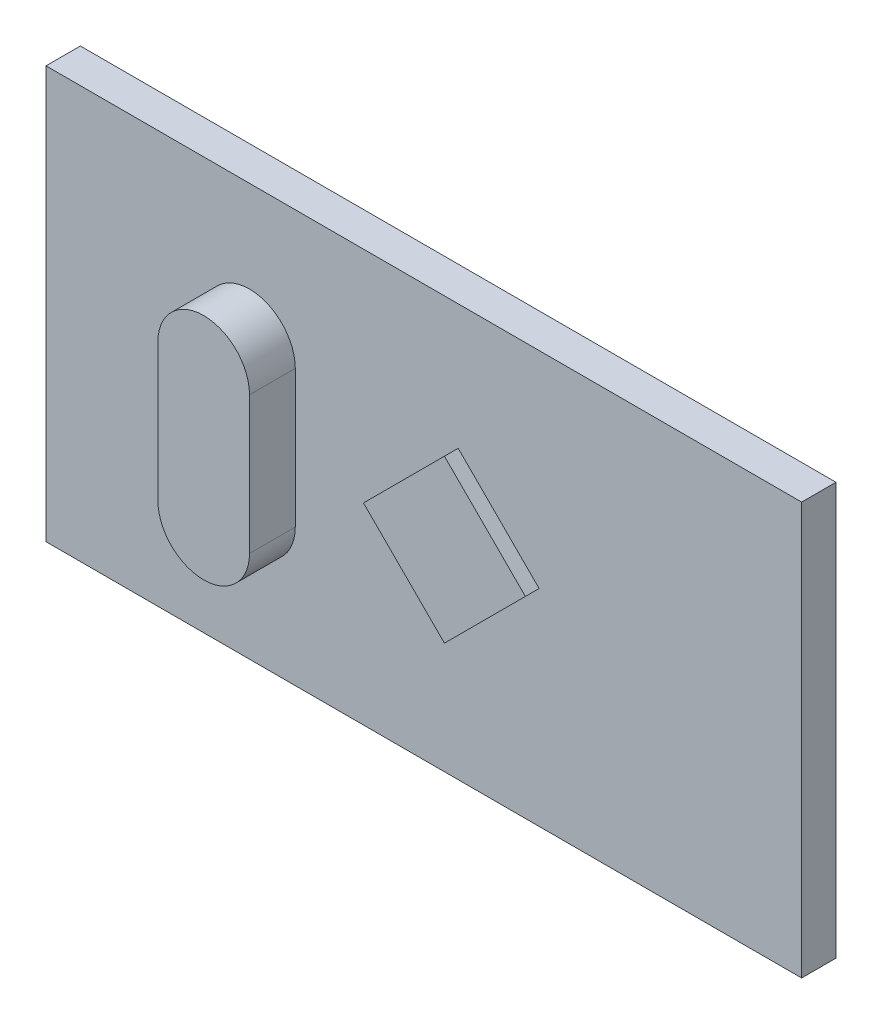
SolidWorks part; units mm, degrees
ref_plane "Спереди" through (0, 0, 0) normal (0, 0, 1) x (1, 0, 0)
ref_plane "Сверху" through (0, 0, 0) normal (0, 1, 0) x (1, 0, 0)
ref_plane "Справа" through (0, 0, 0) normal (1, 0, 0) x (0, 0, -1)
sketch "Эскиз1" plane through (0, 0, 0) normal (0, 0, 1) x (1, 0, 0)
  line L1 (0, 0) -> (33, 0)
  line L2 (0, 0) -> (0, 18)
  line L3 (0, 18) -> (33, 18)
  line L4 (33, 0) -> (33, 18)
  dimension "D1" = 18
  dimension "D2" = 33
extrude "Бобышка-Вытянуть1" add sketch "Эскиз1" along normal blind 1.5
sketch "Эскиз2" plane through (0, 0, 1.5) normal (0, 0, 1) x (1, 0, 0)
  line L0 (33, 9) -> (0, 9) construction
  line L1 (33, 0) -> (33, 18) construction
  line L2 (0, 18) -> (0, 0) construction
  line L3 (18, 9) -> (18, 15.0621) construction
  line L4 (18, 12.5355) -> (21.5355, 9)
  line L5 (14.4645, 9) -> (18, 12.5355)
  line L6 (21.5355, 9) -> (18, 5.4645)
  line L7 (18, 5.4645) -> (14.4645, 9)
  point P19 (18, 9)
  dimension "D1" = 45
  dimension "D2" = 5
  dimension "D4" = 15
  dimension "D3" = 4
extrude "Бобышка-Вытянуть2" add sketch "Эскиз2" along normal blind 0.6
sketch "Эскиз3" plane through (0, 0, 1.5) normal (0, 0, 1) x (1, 0, 0)
  line L0 (8.8863, 6) -> (8.8863, 12) construction
  line L1 (6.8863, 6) -> (6.8863, 12)
  line L2 (10.8863, 6) -> (10.8863, 12)
  line L3 (0, 9) -> (35.1378, 9) construction
  line L4 (0, 18) -> (0, 0) construction
  arc A0 (6.8863, 6) -> (10.8863, 6) centre (8.8863, 6) ccw
  arc A1 (10.8863, 12) -> (6.8863, 12) centre (8.8863, 12) ccw
  point P2 (8.8863, 9)
  dimension "D1" = 4
  dimension "D2" = 6
extrude "Бобышка-Вытянуть3" add sketch "Эскиз3" along normal blind 2
